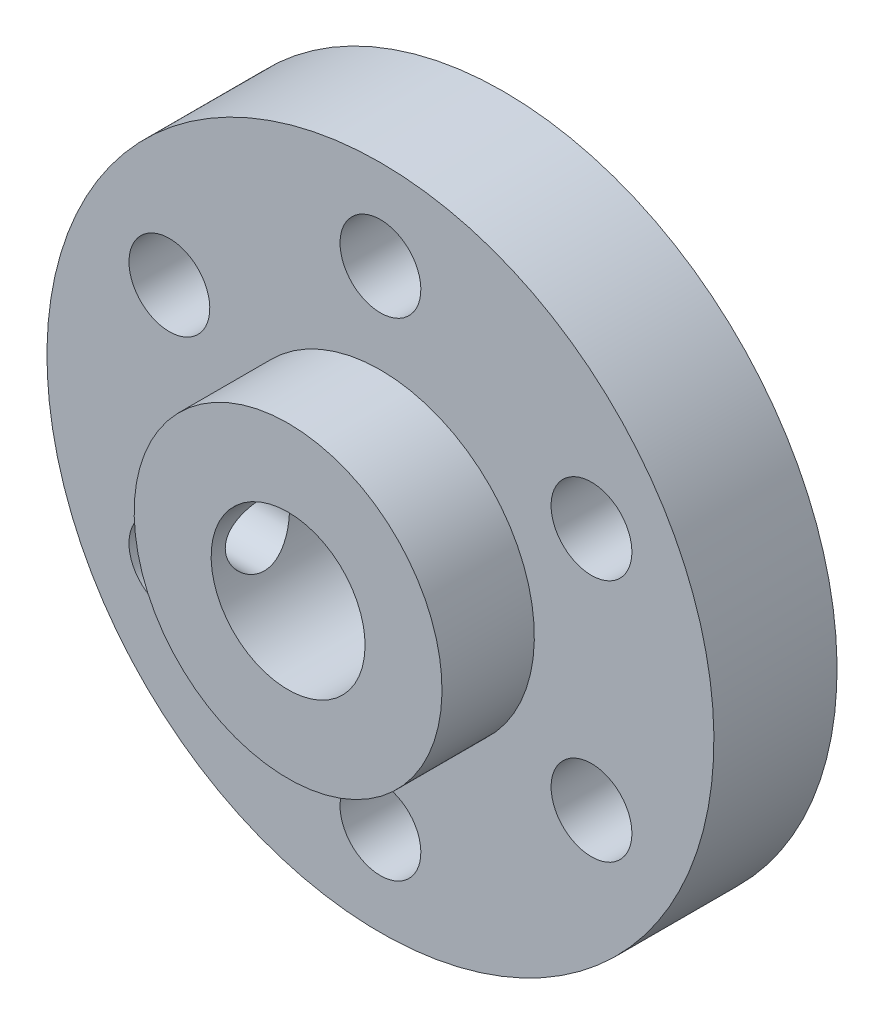
SolidWorks part; units mm, degrees
ref_plane "Front Plane" through (0, 0, 0) normal (0, 0, 1) x (1, 0, 0)
ref_plane "Top Plane" through (0, 0, 0) normal (0, 1, 0) x (1, 0, 0)
ref_plane "Right Plane" through (0, 0, 0) normal (1, 0, 0) x (0, 0, -1)
sketch "Sketch1" plane through (0, 0, 0) normal (1, 0, 0) x (0, 0, -1)
  line L0 (-6.1732, 0) -> (-9.9474, 0) construction
  line L1 (0, 3) -> (-8.4, 3)
  line L2 (-8.4, 3) -> (-8.4, 6)
  line L3 (-8.4, 6) -> (-4.8, 6)
  line L4 (-4.8, 6) -> (-4.8, 13)
  line L5 (-4.8, 13) -> (0, 13)
  line L6 (0, 13) -> (0, 3)
  dimension "D1" = 3
  dimension "D2" = 3
  dimension "D3" = 10
  dimension "D4" = 4.8
  dimension "D5" = 3.6
  dimension "D6" = 0
revolve "Revolve1" add sketch "Sketch1" angle 360 about L0
sketch "Sketch2" plane through (0, 0, 0) normal (1, 0, 0) x (0, 0, -1)
  line L0 (-4.8, 6) -> (-4.8, -6) construction
  line L1 (0, -13) -> (0, 13) construction
  circle A0 centre (-2.4, 0) radius 1.25
  circle A1 centre (-6.6, 0) radius 1.25
  dimension "D1" = 1.8
  dimension "D2" = 2.4
  dimension "D3" = 2.5
  dimension "D4" = 2.5
sketch "Sketch9" plane through (0, 0, 4.8) normal (0, 0, 1) x (1, 0, 0)
  line L0 (0, 0) -> (-17.3081, 0) construction
  line L1 (0, 0) -> (-13.813, -7.9749) construction
  circle A0 centre (-8.2272, -4.75) radius 1
  circle A2 centre (0, 0) radius 13 construction
  circle A4 centre (-8.2272, 4.75) radius 1
  circle A5 centre (0, 9.5) radius 1
  circle A6 centre (8.2272, 4.75) radius 1
  circle A7 centre (8.2272, -4.75) radius 1
  circle A8 centre (0, -9.5) radius 1
  point P21 (0, 0)
  dimension "D1" = 2
  dimension "D2" = 9.5
  dimension "D3" = 30
  dimension "D4" = 0
  dimension "D5" = 6
hole_wizard "Tap Drill for M3 Helicoil1" positions "3DSketch7" profile "Sketch11" hole size "M3x0.5" standard "ANSI Metric"
sketch3d "3DSketch7"
  point P0 (0, -9.5, 4.8)
  point P3 (8.2272, -4.75, 4.8)
  point P6 (8.2272, 4.75, 4.8)
  point P9 (0, 9.5, 4.8)
  point P12 (-8.2272, 4.75, 4.8)
  point P15 (-8.2272, -4.75, 4.8)
sketch "Sketch11" plane through (0, -9.5, 4.8) normal (1, 0, 0) x (0, -1, 0)
  line L0 (0, 0) -> (0, 10.9464)
  line L1 (0, 10.9464) -> (1.575, 10)
  line L2 (1.575, 10) -> (1.575, 0)
  line L5 (1.575, 0) -> (0, 0)
  line L10 (0, 10.9464) -> (-1.575, 10) construction
  line L11 (0, -6.35) -> (0, 107.95) construction
  dimension "Hole Dia." = 3.15
  dimension "Hole Depth" = 10
  dimension "Drill Angle" = 118
ref_plane "Plane1" through (-6, 0, 0) normal (-1, 0, 0) x (0, 0, 1)
ref_plane "Plane2" through (-13, 0, 0) normal (-1, 0, 0) x (0, 0, 1)
extrude "Cut-Extrude3" cut sketch "Sketch2" against normal up to next
